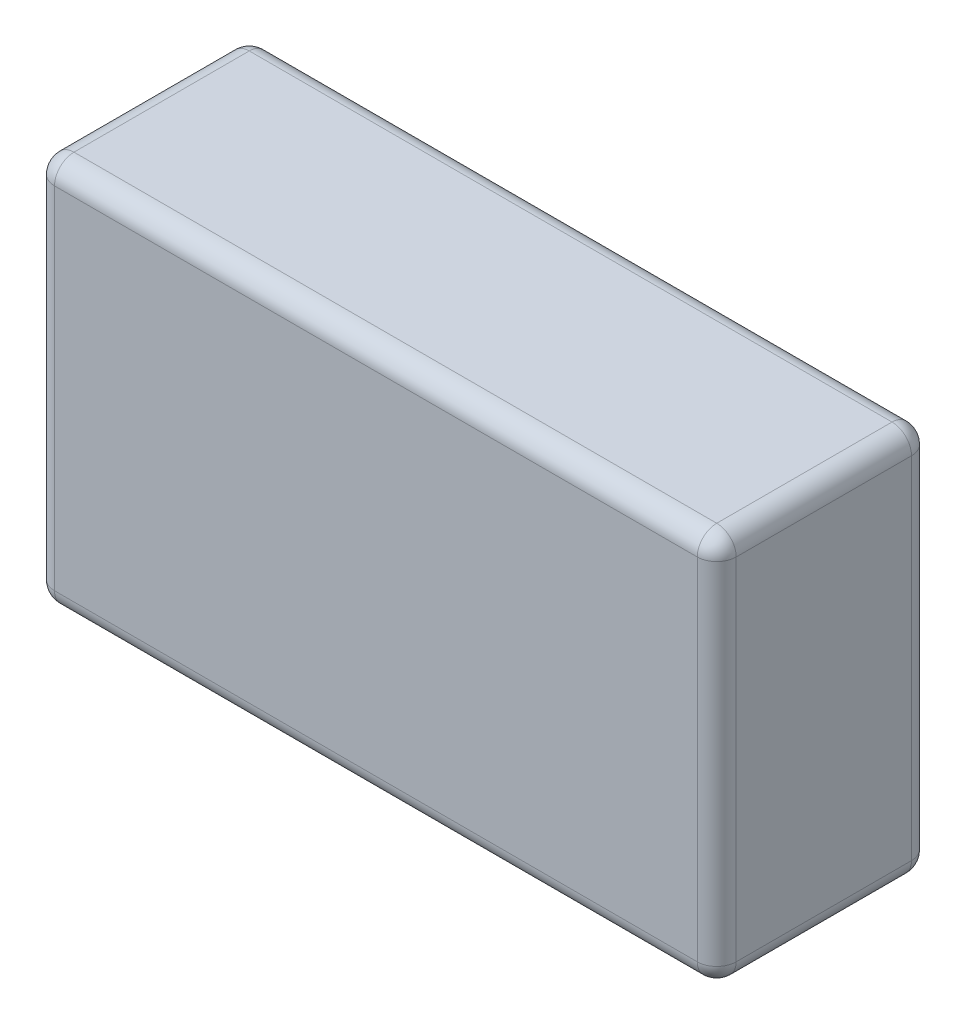
SolidWorks part; units mm, degrees
ref_plane "前视基准面" through (0, 0, 0) normal (0, 0, 1) x (1, 0, 0)
ref_plane "上视基准面" through (0, 0, 0) normal (0, 1, 0) x (1, 0, 0)
ref_plane "右视基准面" through (0, 0, 0) normal (1, 0, 0) x (0, 0, -1)
other "Configuration Table"
sketch "草图1" plane through (0, 0, 0) normal (0, 0, 1) x (1, 0, 0)
  line L1 (-35, -20) -> (35, -20)
  line L2 (-35, -20) -> (-35, 20)
  line L3 (-35, 20) -> (35, 20)
  line L4 (35, -20) -> (35, 20)
  line L5 (-35, -20) -> (35, 20) construction
  line L6 (-35, 20) -> (35, -20) construction
  point P0 (0, 0)
extrude "凸台-拉伸1" add sketch "草图1" along normal mid plane 22
sketch "草图2" plane through (0, 0, 0) normal (0, 0, 1) x (1, 0, 0)
  line L1 (-30, 19) -> (30, 19)
  line L2 (-30, 19) -> (-30, 25)
  line L3 (-30, 25) -> (30, 25)
  line L4 (30, 19) -> (30, 25)
  line L5 (-30, 19) -> (30, 25) construction
  line L6 (-30, 25) -> (30, 19) construction
fillet "圆角1" radius 2 12 edges at (35, 0, -11) (0, 20, -11) (-35, 0, -11) (0, -20, -11) (35, 0, 11) (0, 20, 11) (-35, 0, 11) (0, -20, 11) (35, -20, 0) (-35, -20, 0) (-35, 20, 0) (35, 20, 0)
